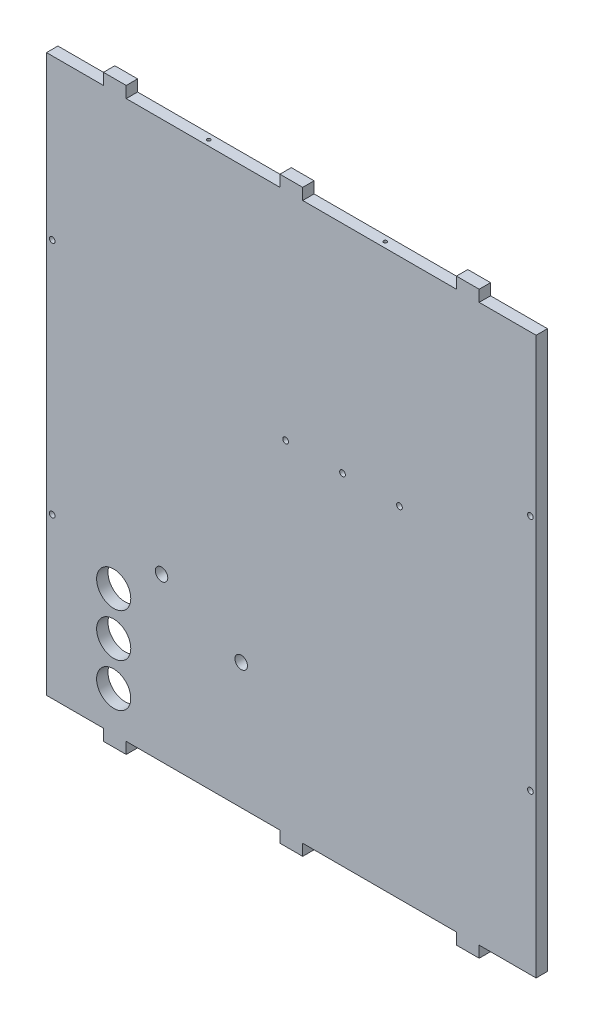
SolidWorks part; units mm, degrees
ref_plane "Ebene vorne" through (0, 0, 0) normal (0, 0, 1) x (1, 0, 0)
ref_plane "Ebene oben" through (0, 0, 0) normal (0, 1, 0) x (1, 0, 0)
ref_plane "Ebene rechts" through (0, 0, 0) normal (1, 0, 0) x (0, 0, -1)
sketch "Skizze1" plane through (0, 0, 0) normal (0, 0, 1) x (1, 0, 0)
  line L0 (0, 0) -> (0, -83406.5938) construction
  line L1 (0, 0) -> (83406.5938, 0) construction
  line L2 (55, 67.225) -> (75, 67.225)
  line L3 (-100, -67.225) -> (100, -67.225)
  line L4 (10.5, -37.555) -> (10.5, -42.555)
  line L5 (-100, 67.225) -> (-85, 67.225)
  line L6 (50.5, -37.555) -> (55.5, -37.555)
  line L7 (-100, -67.225) -> (100, 67.225) construction
  line L8 (-100, 67.225) -> (100, -67.225) construction
  line L9 (100, 47.225) -> (100, 67.225)
  line L10 (75, 67.225) -> (75, 72.225)
  line L11 (75, 72.225) -> (85, 72.225)
  line L12 (85, 67.225) -> (85, 72.225)
  line L13 (85, 67.225) -> (100, 67.225)
  line L14 (45, 67.225) -> (45, 72.225)
  line L15 (45, 72.225) -> (55, 72.225)
  line L16 (55, 67.225) -> (55, 72.225)
  line L17 (50.5, -37.555) -> (50.5, -42.555)
  line L18 (50.5, -42.555) -> (55.5, -42.555)
  line L19 (55.5, -37.555) -> (55.5, -42.555)
  line L20 (15.5, -42.555) -> (10.5, -42.555)
  line L21 (100, 47.225) -> (105, 47.225)
  line L22 (15.5, -37.555) -> (15.5, -42.555)
  line L23 (100, 37.225) -> (105, 37.225)
  line L24 (105, 47.225) -> (105, 37.225)
  line L25 (15.5, -37.555) -> (10.5, -37.555)
  line L26 (-75, 67.225) -> (45, 67.225)
  line L27 (100, -47.225) -> (100, -67.225)
  line L29 (-75, 67.225) -> (-75, 72.225)
  line L30 (-75, 72.225) -> (-85, 72.225)
  line L31 (105, -47.225) -> (105, -37.225)
  line L32 (100, -37.225) -> (105, -37.225)
  line L33 (-85, 67.225) -> (-85, 72.225)
  line L34 (100, -47.225) -> (105, -47.225)
  line L38 (100, 37.225) -> (100, -37.225)
  line L44 (-100, 37.225) -> (-100, -37.225)
  line L48 (-100, -47.225) -> (-105, -47.225)
  line L50 (-100, -37.225) -> (-105, -37.225)
  line L51 (-105, -47.225) -> (-105, -37.225)
  line L53 (-100, -47.225) -> (-100, -67.225)
  line L55 (-105, 47.225) -> (-105, 37.225)
  line L56 (-100, 37.225) -> (-105, 37.225)
  line L58 (-100, 47.225) -> (-105, 47.225)
  line L62 (-100, 47.225) -> (-100, 67.225)
  line L63 (33, -37.555) -> (33, -42.555) construction
  line L64 (25.5, -37.555) -> (40.5, -37.555)
  line L65 (25.5, -37.555) -> (25.5, -42.555)
  line L66 (25.5, -42.555) -> (40.5, -42.555)
  line L67 (40.5, -37.555) -> (40.5, -42.555)
  line L68 (105, 0) -> (105, -50000) construction
  point P5 (0, 0)
  dimension "D1" = 134.45
  dimension "D2" = 200
  dimension "D3" = 10
  dimension "D4" = 20
  dimension "D5" = 5
  dimension "D6" = 20
  dimension "D7" = 20
  dimension "D8" = 29.67
  dimension "D9" = 72
  dimension "D10" = 15
  dimension "D11" = 105
  dimension "D12" = 10
  dimension "D13" = 5
  dimension "D14" = 15
extrude "Aufsatz-Linear austragen1" add sketch "Skizze1" along normal blind 5
sketch "Skizze2" plane through (0, 0, 5) normal (0, 0, 1) x (1, 0, 0)
  line L0 (-42, 48.7841) -> (-42, -49951.2159) construction
  line L1 (-80.5107, -3.925) -> (49919.4893, -3.925) construction
  line L2 (-100, 67.225) -> (-85, 67.225) construction
  line L4 (100, 37.225) -> (100, -37.225) construction
  circle A0 centre (-59.5, 4.075) radius 2.75
  circle A1 centre (-24.5, 4.075) radius 2.75 construction
  circle A2 centre (-59.5, -11.925) radius 2.75 construction
  circle A3 centre (-24.5, -11.925) radius 2.75
  dimension "D1" = 5.5
  dimension "D2" = 63.15
  dimension "D3" = 142
  dimension "D4" = 35
  dimension "D5" = 16
extrude "Schnitt-Linear austragen1" cut sketch "Skizze2" against normal through all
sketch "Skizze3" plane through (0, 0, 5) normal (0, 0, 1) x (1, 0, 0)
  line L0 (33, -42.555) -> (33, -17.555) construction
  line L1 (25, -17.555) -> (41, -17.555)
  line L2 (23, -19.555) -> (23, -35.555)
  line L3 (37, -37.555) -> (41, -37.555)
  line L4 (43, -19.555) -> (43, -35.555)
  line L5 (-14.5, -32.225) -> (4.5, -32.225) construction
  line L6 (-17.5, -35.225) -> (-17.5, -54.225) construction
  line L7 (-14.5, -57.225) -> (4.5, -57.225) construction
  line L8 (7.5, -35.225) -> (7.5, -54.225) construction
  line L9 (25.5, -42.555) -> (40.5, -42.555) construction
  line L10 (25.5, -37.555) -> (40.5, -37.555) construction
  line L11 (29, -37.555) -> (25, -37.555)
  line L12 (-66.5, 54.225) -> (-66.5, 35.225)
  line L13 (37, -37.555) -> (29, -37.555)
  line L14 (-5, -32.225) -> (-5, -50032.225) construction
  line L17 (-88.5, 32.225) -> (-69.5, 32.225)
  line L18 (-100, -67.225) -> (100, -67.225) construction
  line L19 (-5, 57.225) -> (49995, 57.225) construction
  line L20 (-100, 67.225) -> (-85, 67.225) construction
  line L21 (-42, 57.225) -> (-42, -49942.775) construction
  line L24 (4.5, 57.225) -> (-14.5, 57.225)
  line L25 (7.5, 54.225) -> (7.5, 35.225)
  line L26 (4.5, 32.225) -> (-14.5, 32.225)
  line L27 (-17.5, 54.225) -> (-17.5, 35.225)
  line L28 (-91.5, 54.225) -> (-91.5, 35.225)
  line L29 (-88.5, 57.225) -> (-69.5, 57.225)
  line L30 (-79, 57.225) -> (-79, -49942.775) construction
  line L31 (-5, 22.3625) -> (49995, 22.3625) construction
  line L32 (4.5, -12.5) -> (-14.5, -12.5) construction
  line L33 (-17.5, -9.5) -> (-17.5, 9.5) construction
  line L34 (4.5, 12.5) -> (-14.5, 12.5) construction
  line L35 (7.5, -9.5) -> (7.5, 9.5) construction
  line L36 (4.5, 32.225) -> (4.5, 12.5) construction
  line L37 (4.5, -12.5) -> (4.5, -32.225) construction
  line L38 (4.5, -32.225) -> (4.5, -12.5) construction
  circle A0 centre (-24.5, -11.925) radius 2.75 construction
  arc A1 (23, -35.555) -> (25, -37.555) centre (25, -35.555) ccw
  arc A2 (43, -35.555) -> (41, -37.555) centre (41, -35.555) cw
  arc A3 (43, -19.555) -> (41, -17.555) centre (41, -19.555) ccw
  arc A4 (25, -17.555) -> (23, -19.555) centre (25, -19.555) ccw
  arc A5 (-17.5, -54.225) -> (-14.5, -57.225) centre (-14.5, -54.225) ccw construction
  arc A6 (7.5, -54.225) -> (4.5, -57.225) centre (4.5, -54.225) cw construction
  arc A8 (7.5, -35.225) -> (4.5, -32.225) centre (4.5, -35.225) ccw construction
  arc A9 (-14.5, -32.225) -> (-17.5, -35.225) centre (-14.5, -35.225) ccw construction
  arc A10 (7.5, 35.225) -> (4.5, 32.225) centre (4.5, 35.225) cw
  arc A11 (-14.5, 32.225) -> (-17.5, 35.225) centre (-14.5, 35.225) cw
  arc A12 (-17.5, 54.225) -> (-14.5, 57.225) centre (-14.5, 54.225) cw
  arc A14 (4.5, 57.225) -> (7.5, 54.225) centre (4.5, 54.225) cw
  arc A15 (-88.5, 57.225) -> (-91.5, 54.225) centre (-88.5, 54.225) ccw
  arc A16 (-66.5, 54.225) -> (-69.5, 57.225) centre (-69.5, 54.225) ccw
  arc A17 (-69.5, 32.225) -> (-66.5, 35.225) centre (-69.5, 35.225) ccw
  arc A18 (-91.5, 35.225) -> (-88.5, 32.225) centre (-88.5, 35.225) ccw
  circle A19 centre (-59.5, 4.075) radius 2.75 construction
  arc A20 (-17.5, -9.5) -> (-14.5, -12.5) centre (-14.5, -9.5) ccw construction
  arc A21 (-14.5, 12.5) -> (-17.5, 9.5) centre (-14.5, 9.5) ccw construction
  arc A22 (7.5, 9.5) -> (4.5, 12.5) centre (4.5, 9.5) ccw construction
  arc A23 (4.5, -12.5) -> (7.5, -9.5) centre (4.5, -9.5) ccw construction
  point P19 (23, -37.555)
  point P22 (43, -37.555)
  point P25 (43, -17.555)
  point P28 (23, -17.555)
  point P52 (43, -37.555)
  point P53 (-5, -32.225)
  point P67 (-17.5, 32.225)
  point P70 (-17.5, 57.225)
  point P73 (7.5, 57.225)
  point P86 (-91.5, 57.225)
  point P87 (-66.5, 57.225)
  point P88 (-66.5, 32.225)
  point P91 (-79, 57.225)
  dimension "D1" = 20
  dimension "D2" = 20
  dimension "D6" = 25
  dimension "D3" = 2
  dimension "D7" = 3
  dimension "D12" = 25
  dimension "D5" = 19.5
  dimension "D15" = 2
  dimension "D17" = 3
  dimension "D18" = 19.5
  dimension "D4" = 10
  dimension "D8" = 25
  dimension "D9" = 25
  dimension "D11" = 10
  dimension "D13" = 0
  dimension "D14" = 8
extrude "Schnitt-Linear austragen2" cut sketch "Skizze3" against normal through all
sketch "Skizze4" plane through (0, 0, 5) normal (0, 0, 1) x (1, 0, 0)
  line L0 (55, 67.225) -> (75, 67.225) construction
  line L1 (100, 47.225) -> (100, 67.225) construction
  line L2 (-100, -67.225) -> (100, -67.225) construction
  line L3 (-80.5, -30.925) -> (49919.5, -30.925) construction
  line L4 (-80.5, -30.925) -> (-80.5, -50030.925) construction
  circle A0 centre (45.5, 53.325) radius 7.5 construction
  circle A1 centre (-80.5, -30.925) radius 7.5
  circle A2 centre (-59.5, 4.075) radius 2.75 construction
  circle A3 centre (-80.5, -11.925) radius 7.5
  circle A4 centre (-80.5, -49.925) radius 7.5
  dimension "D1" = 13.9
  dimension "D3" = 15
  dimension "D5" = 21
  dimension "D6" = 19
  dimension "D2" = 54.5
  dimension "D4" = 36.3
extrude "Schnitt-Linear austragen3" cut sketch "Skizze4" against normal through all
sketch "Skizze5" plane through (0, 0, 5) normal (0, 0, 1) x (1, 0, 0)
  line L0 (-8, -45.225) -> (-8, -3.225) construction
  line L1 (83, -12.225) -> (-8, -12.225) construction
  line L2 (-100, -67.225) -> (100, -67.225) construction
  line L3 (100, 37.225) -> (100, -37.225) construction
  line L4 (-30.2483, -49.225) -> (49969.7517, -49.225) construction
  line L5 (-17.9531, -56.225) -> (49982.0469, -56.225) construction
  line L6 (22.5, -56.9878) -> (22.5, -50056.9878) construction
  line L7 (37.5, -10.225) -> (37.5, -50010.225) construction
  circle A0 centre (-8, -45.225) radius 0.75
  circle A1 centre (-8, -3.225) radius 0.75
  circle A2 centre (83, -12.225) radius 0.75
  circle A3 centre (-15, -56.225) radius 6
  circle A4 centre (0, -56.225) radius 6
  circle A5 centre (15, -56.225) radius 6
  circle A6 centre (30, -56.225) radius 6
  circle A7 centre (45, -56.225) radius 6
  circle A8 centre (60, -56.225) radius 6
  circle A9 centre (75, -56.225) radius 6
  circle A10 centre (90, -56.225) radius 6
  point P36 (37.5, -12.225)
  dimension "D1" = 1.5
  dimension "D9" = 12
  dimension "D2" = 42
  dimension "D4" = 91
  dimension "D3" = 9
  dimension "D5" = 22
  dimension "D6" = 17
  dimension "D7" = 4
  dimension "D10" = 7
  dimension "D11" = 15
  dimension "D8" = 8
extrude "Sensors" cut sketch "Skizze5" against normal through all
sketch "Skizze6" plane through (0, 0, 0) normal (0, 0, -1) x (-1, 0, 0)
  line L0 (100, -67.225) -> (-100, -67.225) construction
  line L1 (160, 47.225) -> (160, 37.225)
  line L2 (100, 67.225) -> (100, -67.225)
  line L3 (100, -67.225) -> (160, -67.225)
  line L4 (160, 67.225) -> (160, 47.225)
  line L6 (100, -37.225) -> (105, -37.225) construction
  line L7 (160, -47.225) -> (160, -67.225)
  line L8 (100, -47.225) -> (105, -47.225) construction
  line L9 (100, 47.225) -> (105, 47.225) construction
  line L10 (100, 37.225) -> (105, 37.225) construction
  line L11 (75, 67.225) -> (-45, 67.225) construction
  line L17 (160, 37.225) -> (160, -37.225)
  line L18 (-30.5, 67.225) -> (100, 67.225)
  line L19 (-30.5, 67.225) -> (-30.5, 177.225)
  line L20 (-30.5, 177.225) -> (160, 177.225)
  line L21 (160, 67.225) -> (160, 177.225)
  line L22 (-100, 47.225) -> (-100, 67.225) construction
  line L23 (160, -37.225) -> (160, -47.225)
  dimension "D1" = 60
  dimension "D2" = 110
  dimension "D3" = 69.5
extrude "Aufsatz-Linear austragen2" add sketch "Skizze6" against normal blind 5
sketch "Skizze7" plane through (0, 0, 0) normal (0, 0, -1) x (-1, 0, 0)
  line L0 (71.5, 32.775) -> (96.5, 32.775) construction
  line L1 (160, -67.225) -> (-100, -67.225) construction
  line L4 (91.5, 54.225) -> (91.5, 35.225) construction
  line L5 (46.5, 32.775) -> (71.5, 32.775) construction
  line L6 (122.7956, 60.525) -> (50122.7956, 60.525) construction
  circle A0 centre (71.5, 32.775) radius 1.25
  circle A1 centre (96.5, 32.775) radius 1.25
  circle A4 centre (46.5, 32.775) radius 1.25
  dimension "D3" = 2.5
  dimension "D1" = 100
  dimension "D2" = 25
  dimension "D4" = 20
extrude "Schnitt-Linear austragen5" cut sketch "Skizze7" against normal through all
sketch "Sketch1" plane through (0, 0, 5) normal (0, 0, 1) x (1, 0, 0)
  line L1 (30.5, 177.225) -> (100, 177.225)
  line L2 (30.5, 177.225) -> (30.5, 67.225)
  line L3 (30.5, 67.225) -> (100, 67.225)
  line L4 (100, 177.225) -> (100, 67.225)
extrude "Boss-Extrude1" add sketch "Sketch1" against normal blind 5
sketch "Skizze9" plane through (0, 0, 5) normal (0, 0, 1) x (1, 0, 0)
  line L0 (-33.1526, 41.015) -> (49966.8474, 41.015) construction
  line L1 (38.5, 36.3664) -> (38.5, 48631.464) construction
  line L5 (-2, 7.1234) -> (-2, 89.5656) construction
  line L7 (-17.5, 54.225) -> (-17.5, 35.225) construction
  line L8 (4.5, 57.225) -> (-14.5, 57.225) construction
  circle A0 centre (8, 71.515) radius 0.75
  circle A1 centre (69, 71.515) radius 0.75
  circle A2 centre (8, 10.515) radius 0.75
  circle A3 centre (69, 10.515) radius 0.75
  circle A4 centre (-2, 5.015) radius 6
  circle A5 centre (-2, 29.015) radius 6
  circle A6 centre (-2, 53.015) radius 6
  circle A7 centre (-2, 77.015) radius 6
  dimension "D1" = 1.5
  dimension "D8" = 12
  dimension "D2" = 61
  dimension "D3" = 61
  dimension "D7" = 24
  dimension "D5" = 15.5
  dimension "D9" = 4.21
  dimension "D4" = 10
  dimension "D6" = 4
extrude "DiscreteChannel" cut sketch "Skizze9" against normal through all
sketch "Skizze10" plane through (0, 0, 5) normal (0, 0, 1) x (1, 0, 0)
  line L0 (-50, 127.2474) -> (-50, -49872.7526) construction
  line L1 (-69.94, 115.225) -> (49930.06, 115.225) construction
  line L4 (-50.8687, 166.225) -> (49949.1313, 166.225) construction
  line L5 (-75.5, 136.225) -> (49924.5, 136.225) construction
  line L6 (-72.5, 172.225) -> (-27.5, 172.225) construction
  line L7 (-72.5, 166.225) -> (-72.5, 151.225) construction
  line L8 (-160, 177.225) -> (100, 177.225) construction
  line L9 (100, 47.225) -> (100, 177.225) construction
  circle A0 centre (-4, 136.225) radius 0.75
  circle A1 centre (-4, 94.225) radius 0.75
  circle A2 centre (-96, 136.225) radius 0.75
  circle A3 centre (-96, 94.225) radius 0.75
  circle A4 centre (-72.5, 166.225) radius 6
  circle A5 centre (-2, 5.015) radius 6 construction
  circle A6 centre (-57.5, 166.225) radius 6
  circle A7 centre (-42.5, 166.225) radius 6
  circle A8 centre (-27.5, 166.225) radius 6
  circle A9 centre (-27.5, 151.225) radius 6
  circle A10 centre (-42.5, 151.225) radius 6
  circle A11 centre (-57.5, 151.225) radius 6
  circle A12 centre (-72.5, 151.225) radius 6
  point P20 (-50, 172.225)
  dimension "D6" = 4
  dimension "D5" = 1.5
  dimension "D1" = 42
  dimension "D2" = 92
  dimension "D7" = 15
  dimension "D9" = 30
  dimension "D8" = 15
  dimension "D4" = 11
  dimension "D10" = 150
  dimension "D3" = 2
extrude "ContChannel" cut sketch "Skizze10" against normal through all
sketch "Sketch2" plane through (0, 0, 5) normal (0, 0, 1) x (1, 0, 0)
  line L0 (-14.5, 32.225) -> (-7.0691, 32.225) construction
  line L1 (3.0691, 32.225) -> (4.5, 32.225) construction
  line L2 (7.5, 35.225) -> (7.5, 54.225) construction
  line L3 (4.5, 57.225) -> (2.275, 57.225) construction
  line L4 (-6.275, 57.225) -> (-14.5, 57.225) construction
  line L5 (-17.5, 54.225) -> (-17.5, 35.225) construction
  line L6 (-14.5, 32.225) -> (-7.0691, 32.225)
  line L7 (3.0691, 32.225) -> (4.5, 32.225)
  line L8 (7.5, 35.225) -> (7.5, 54.225)
  line L9 (4.5, 57.225) -> (2.275, 57.225)
  line L10 (-6.275, 57.225) -> (-14.5, 57.225)
  line L11 (-17.5, 54.225) -> (-17.5, 35.225)
  arc A0 (-17.5, 35.225) -> (-14.5, 32.225) centre (-14.5, 35.225) ccw construction
  arc A1 (-7.0691, 32.225) -> (3.0691, 32.225) centre (-2, 29.015) ccw construction
  arc A2 (4.5, 32.225) -> (7.5, 35.225) centre (4.5, 35.225) ccw construction
  arc A3 (7.5, 54.225) -> (4.5, 57.225) centre (4.5, 54.225) ccw construction
  arc A4 (2.275, 57.225) -> (-6.275, 57.225) centre (-2, 53.015) ccw construction
  arc A5 (-14.5, 57.225) -> (-17.5, 54.225) centre (-14.5, 54.225) ccw construction
  arc A6 (-17.5, 35.225) -> (-14.5, 32.225) centre (-14.5, 35.225) ccw
  arc A7 (-7.0691, 32.225) -> (3.0691, 32.225) centre (-2, 29.015) ccw construction
  arc A8 (4.5, 32.225) -> (7.5, 35.225) centre (4.5, 35.225) ccw
  arc A9 (7.5, 54.225) -> (4.5, 57.225) centre (4.5, 54.225) ccw
  arc A10 (2.275, 57.225) -> (-6.275, 57.225) centre (-2, 53.015) ccw construction
  arc A11 (-14.5, 57.225) -> (-17.5, 54.225) centre (-14.5, 54.225) ccw
  arc A12 (-7.0691, 32.225) -> (3.0691, 32.225) centre (-2, 29.015) cw
  arc A13 (-6.275, 57.225) -> (2.275, 57.225) centre (-2, 53.015) ccw
extrude "Boss-Extrude2" add sketch "Sketch2" against normal blind 5
sketch "Skizze8" plane through (0, 0, 5) normal (0, 0, 1) x (1, 0, 0)
  line L0 (-165.5788, 126.725) -> (49834.4212, 126.725) construction
  line L1 (78, 176.1292) -> (78, 50176.1292) construction
  line L2 (-160, 177.225) -> (100, 177.225) construction
  line L3 (100, 47.225) -> (100, 177.225) construction
  line L5 (62.5, 100.225) -> (93.5, 100.225) construction
  circle A0 centre (62.5, 153.225) radius 0.75
  circle A1 centre (93.5, 153.225) radius 0.75
  circle A2 centre (62.5, 100.225) radius 0.75
  circle A3 centre (93.5, 100.225) radius 0.75
  circle A4 centre (78, 86.225) radius 7.5
  circle A5 centre (-80.5, -11.925) radius 7.5 construction
  circle A6 centre (78, 167.225) radius 7.5
  dimension "D1" = 1.5
  dimension "D2" = 53
  dimension "D3" = 31
  dimension "D4" = 14
  dimension "D5" = 10
  dimension "D6" = 6.5
extrude "StepDownConverter" cut sketch "Skizze8" against normal through all
sketch "Sketch3" plane through (0, 0, 5) normal (0, 0, 1) x (1, 0, 0)
  line L0 (46.6666, 126.725) -> (50046.6666, 126.725) construction
  line L1 (100, 47.225) -> (100, 177.225) construction
  line L2 (93.5, 153.225) -> (93.5, 100.225) construction
  line L3 (78, 167.225) -> (50078, 167.225) construction
  circle A0 centre (21.85, 147.68) radius 0.75
  circle A1 centre (87.89, 102.59) radius 0.75
  circle A2 centre (87.89, 150.86) radius 0.75
  circle A3 centre (21.85, 105.77) radius 0.75
  circle A4 centre (13, 167.225) radius 5
  circle A5 centre (28, 167.225) radius 5
  circle A6 centre (43, 167.225) radius 5
  circle A7 centre (58, 167.225) radius 5
  circle A8 centre (78, 167.225) radius 7.5 construction
  circle A9 centre (13, 86.225) radius 5
  point P10 (93.5, 126.725)
  dimension "D4" = 1.5
  dimension "D6" = 10
  dimension "D1" = 66.04
  dimension "D2" = 41.91
  dimension "D3" = 3.18
  dimension "D5" = 12.11
  dimension "D8" = 15
  dimension "D9" = 20
  dimension "D7" = 4
extrude "BBB" cut sketch "Sketch3" against normal blind 5
sketch "Sketch4" plane through (0, 0, 5) normal (0, 0, 1) x (1, 0, 0)
  line L0 (-88.5, 32.225) -> (-72.6225, 32.225) construction
  line L1 (-70.3775, 32.225) -> (-69.5, 32.225) construction
  line L2 (-66.5, 35.225) -> (-66.5, 54.225) construction
  line L3 (-69.5, 57.225) -> (-88.5, 57.225) construction
  line L4 (-91.5, 54.225) -> (-91.5, 35.225) construction
  line L5 (-88.5, 32.225) -> (-72.6225, 32.225)
  line L6 (-70.3775, 32.225) -> (-69.5, 32.225)
  line L7 (-66.5, 35.225) -> (-66.5, 54.225)
  line L8 (-69.5, 57.225) -> (-88.5, 57.225)
  line L9 (-91.5, 54.225) -> (-91.5, 35.225)
  arc A0 (-91.5, 35.225) -> (-88.5, 32.225) centre (-88.5, 35.225) ccw construction
  arc A1 (-72.6225, 32.225) -> (-70.3775, 32.225) centre (-71.5, 32.775) ccw construction
  arc A2 (-69.5, 32.225) -> (-66.5, 35.225) centre (-69.5, 35.225) ccw construction
  arc A3 (-66.5, 54.225) -> (-69.5, 57.225) centre (-69.5, 54.225) ccw construction
  arc A4 (-88.5, 57.225) -> (-91.5, 54.225) centre (-88.5, 54.225) ccw construction
  arc A5 (-91.5, 35.225) -> (-88.5, 32.225) centre (-88.5, 35.225) ccw
  arc A6 (-72.6225, 32.225) -> (-70.3775, 32.225) centre (-71.5, 32.775) ccw construction
  arc A7 (-69.5, 32.225) -> (-66.5, 35.225) centre (-69.5, 35.225) ccw
  arc A8 (-66.5, 54.225) -> (-69.5, 57.225) centre (-69.5, 54.225) ccw
  arc A9 (-88.5, 57.225) -> (-91.5, 54.225) centre (-88.5, 54.225) ccw
  arc A10 (-72.6225, 32.225) -> (-70.3775, 32.225) centre (-71.5, 32.775) cw
extrude "Boss-Extrude3" add sketch "Sketch4" against normal blind 5
sketch "Sketch5" plane through (0, 0, 5) normal (0, 0, 1) x (1, 0, 0)
  line L0 (-160, -67.225) -> (100, -67.225) construction
  line L1 (-160, 177.225) -> (-105, 177.225)
  line L2 (-160, 177.225) -> (-160, -67.225)
  line L3 (-160, -67.225) -> (-105, -67.225)
  line L4 (-105, 177.225) -> (-105, -67.225)
  line L5 (100, 47.225) -> (100, 177.225) construction
  dimension "D1" = 205
extrude "Cut-Extrude2" cut sketch "Sketch5" against normal blind 5
sketch "Sketch6" plane through (0, 0, 5) normal (0, 0, 1) x (1, 0, 0)
  line L0 (-105, 82.775) -> (49895, 82.775) construction
  line L2 (-105, -67.225) -> (-105, 177.225) construction
  line L3 (-95, 82.775) -> (-95, -49917.225) construction
  circle A0 centre (-96.5, 32.775) radius 1.25 construction
  circle A1 centre (-95, 82.775) radius 5
  circle A2 centre (-80, 82.775) radius 5
  circle A3 centre (-95, -32.225) radius 5
  circle A4 centre (-65, 82.775) radius 5
  dimension "D2" = 10
  dimension "D1" = 50
  dimension "D4" = 10
  dimension "D5" = 15
  dimension "D6" = 115
  dimension "D3" = 3
extrude "Cut-Extrude3" cut sketch "Sketch6" against normal blind 5
sketch "Sketch7" plane through (0, 0, 5) normal (0, 0, 1) x (1, 0, 0)
  line L0 (100, 47.225) -> (100, 177.225) construction
  line L1 (100, 157.225) -> (105, 157.225)
  line L2 (100, 157.225) -> (100, 147.225)
  line L3 (100, 147.225) -> (105, 147.225)
  line L4 (105, 157.225) -> (105, 147.225)
  line L5 (100, -37.225) -> (105, -37.225) construction
  line L6 (-105, 177.225) -> (100, 177.225) construction
  dimension "D1" = 10
  dimension "D2" = 20
extrude "Boss-Extrude4" add sketch "Sketch7" against normal blind 5
sketch "Sketch8" plane through (0, 0, 5) normal (0, 0, 1) x (1, 0, 0)
  line L0 (-105, -67.225) -> (100, -67.225) construction
  line L1 (-85, -67.225) -> (-75, -67.225)
  line L2 (-85, -67.225) -> (-85, -72.225)
  line L3 (-85, -72.225) -> (-75, -72.225)
  line L4 (-75, -67.225) -> (-75, -72.225)
  line L5 (-75, -67.225) -> (70, -67.225) construction
  line L6 (-7.5, -67.225) -> (2.5, -67.225)
  line L7 (-7.5, -67.225) -> (-7.5, -72.225)
  line L8 (-7.5, -72.225) -> (2.5, -72.225)
  line L9 (2.5, -67.225) -> (2.5, -72.225)
  line L10 (70, -67.225) -> (80, -67.225)
  line L11 (70, -67.225) -> (70, -72.225)
  line L12 (70, -72.225) -> (80, -72.225)
  line L13 (80, -67.225) -> (80, -72.225)
  line L14 (-2.5, -67.225) -> (-2.5, -106.7893) construction
  line L15 (-105, -67.225) -> (-105, 177.225) construction
  line L16 (100, -47.225) -> (100, -67.225) construction
  line L17 (-105, 55) -> (49895, 55) construction
  line L18 (70, 182.225) -> (80, 182.225)
  line L19 (80, 177.225) -> (80, 182.225)
  line L20 (70, 177.225) -> (80, 177.225)
  line L21 (70, 177.225) -> (70, 182.225)
  line L22 (-7.5, 182.225) -> (2.5, 182.225)
  line L23 (-7.5, 177.225) -> (2.5, 177.225)
  line L24 (-7.5, 177.225) -> (-7.5, 182.225)
  line L25 (-85, 177.225) -> (-75, 177.225)
  line L26 (-75, 177.225) -> (-75, 182.225)
  line L27 (-85, 182.225) -> (-75, 182.225)
  line L28 (-85, 177.225) -> (-85, 182.225)
  line L29 (2.5, 177.225) -> (2.5, 182.225)
  point P22 (-105, 55)
  dimension "D1" = 5
  dimension "D2" = 10
  dimension "D3" = 20
  dimension "D4" = 20
extrude "Boss-Extrude5" add sketch "Sketch8" against normal blind 5
sketch "Sketch9" plane through (0, 0, 0) normal (0, 0, -1) x (-1, 0, 0)
  line L0 (-80, -67.225) -> (-100, -67.225) construction
  line L1 (105, 177.225) -> (-105, 177.225)
  line L2 (105, 177.225) -> (105, -67.225)
  line L3 (105, -67.225) -> (-105, -67.225)
  line L4 (-105, 177.225) -> (-105, -67.225)
  line L5 (-105, -47.225) -> (-105, -37.225) construction
  circle A0 centre (59.5, 4.075) radius 2.75 construction
  circle A1 centre (24.5, -11.925) radius 2.75 construction
  circle A2 centre (59.5, 4.075) radius 2.75
  circle A3 centre (24.5, -11.925) radius 2.75
  circle A4 centre (80.5, -49.925) radius 7.5 construction
  circle A5 centre (80.5, -30.925) radius 7.5 construction
  circle A6 centre (80.5, -11.925) radius 7.5 construction
  circle A7 centre (80.5, -49.925) radius 7.5
  circle A8 centre (80.5, -30.925) radius 7.5
  circle A9 centre (80.5, -11.925) radius 7.5
extrude "Boss-Extrude6" add sketch "Sketch9" against normal blind 5
sketch "Sketch10" plane through (0, 0, 0) normal (0, 0, -1) x (-1, 0, 0)
  line L0 (-61.136, 82.225) -> (49938.864, 82.225) construction
  line L1 (-105, 177.225) -> (-105, -67.225) construction
  line L2 (-80, 177.225) -> (-105, 177.225) construction
  circle A0 centre (-45, 82.225) radius 1.25
  circle A1 centre (-20, 82.225) radius 1.25
  circle A2 centre (5, 82.225) radius 1.25
  dimension "D2" = 2.5
  dimension "D3" = 25
  dimension "D4" = 60
  dimension "D5" = 95
  dimension "D1" = 3
extrude "Cut-Extrude4" cut sketch "Sketch10" against normal blind 5
sketch "Sketch11" plane through (0, 0, 0) normal (0, 0, -1) x (-1, 0, 0)
  line L0 (0, 182.225) -> (0, -49817.775) construction
  line L2 (-102.5, 177.225) -> (-102.5, -49822.775) construction
  line L4 (105, 55) -> (50105, 55) construction
  line L5 (105, -67.225) -> (105, 177.225) construction
  line L6 (-105, 177.225) -> (-105, -67.225) construction
  line L7 (-80, 177.225) -> (-105, 177.225) construction
  circle A0 centre (-102.5, 107.225) radius 1.25
  circle A1 centre (-102.5, 2.775) radius 1.25
  circle A2 centre (102.5, 2.775) radius 1.25
  circle A3 centre (102.5, 107.225) radius 1.25
  point P13 (105, 55)
  dimension "D2" = 2.5
  dimension "D3" = 70
  dimension "D1" = 2.5
  dimension "D4" = 2.5
extrude "Cut-Extrude5" cut sketch "Sketch11" against normal through all
sketch "Sketch12" plane through (0, 177.225, 0) normal (0, 1, 0) x (1, 0, 0)
  line L0 (70, -2.5) -> (2.5, -2.5) construction
  line L1 (70, 0) -> (70, -5) construction
  line L2 (2.5, 0) -> (2.5, -5) construction
  line L3 (2.5, -2.5) -> (-7.5, -2.5) construction
  line L4 (-7.5, 0) -> (-7.5, -5) construction
  line L5 (-7.5, -2.5) -> (-75, -2.5) construction
  line L6 (-75, 0) -> (-75, -5) construction
  circle A0 centre (-41.25, -2.5) radius 0.75
  circle A1 centre (36.25, -2.5) radius 0.75
  dimension "D1" = 1.5
extrude "Cut-Extrude6" cut sketch "Sketch12" against normal blind 10
ref_plane "Plane1" through (0, 55, 0) normal (0, 1, 0) x (1, 0, 0)
mirror "Mirror1" about plane through (0, 55, 0) normal (0, 1, 0) of "Cut-Extrude6"
sketch "Sketch13" plane through (-105, 0, 0) normal (-1, 0, 0) x (0, 0, 1)
  line L4 (5, -67.225) -> (5, 177.225)
  line L5 (5, 177.225) -> (0, 177.225)
  line L6 (0, 177.225) -> (0, -67.225)
  line L7 (0, -67.225) -> (5, -67.225)
  line L8 (5, -67.225) -> (5, 177.225)
  line L9 (5, 177.225) -> (0, 177.225)
  line L10 (0, 177.225) -> (0, -67.225)
  line L11 (0, -67.225) -> (5, -67.225)
  dimension "D1" = 0
extrude "Boss-Extrude7" add sketch "Sketch13" along normal blind 5
sketch "Sketch14" plane through (0, 0, 0) normal (0, 0, -1) x (-1, 0, 0)
  circle A0 centre (102.5, 2.775) radius 1.25 construction
  circle A1 centre (102.5, 107.225) radius 1.25 construction
  circle A2 centre (102.5, 2.775) radius 1.25
  circle A3 centre (102.5, 107.225) radius 1.25
  circle A4 centre (107.5, 2.775) radius 1.25
  circle A5 centre (107.5, 107.225) radius 1.25
  dimension "D2" = 5
  dimension "D1" = 2
extrude "Cut-Extrude7" cut sketch "Sketch14" against normal blind 5
sketch "Sketch15" plane through (0, 0, 0) normal (0, 0, -1) x (-1, 0, 0)
  circle A0 centre (102.5, 2.775) radius 1.25 construction
  circle A1 centre (102.5, 107.225) radius 1.25 construction
  circle A2 centre (102.5, 2.775) radius 1.25
  circle A3 centre (102.5, 107.225) radius 1.25
extrude "Boss-Extrude8" add sketch "Sketch15" against normal blind 5
equation "\"m3-gewinde\"= 1.5"
equation "\"m3-durchgang\"= 2.5"
equation "\"D1@Skizze5\"=\"m3-gewinde\""
equation "\"stecker-durchgang\"= 12"
equation "\"D9@Skizze5\"=\"stecker-durchgang\""
equation "\"D3@Skizze7\"=\"m3-durchgang\""
equation "\"D1@Skizze8\"=\"m3-gewinde\""
equation "\"D1@Skizze9\"=\"m3-gewinde\""
equation "\"D8@Skizze9\"=\"stecker-durchgang\""
equation "\"D5@Skizze10\"=\"m3-gewinde\""
